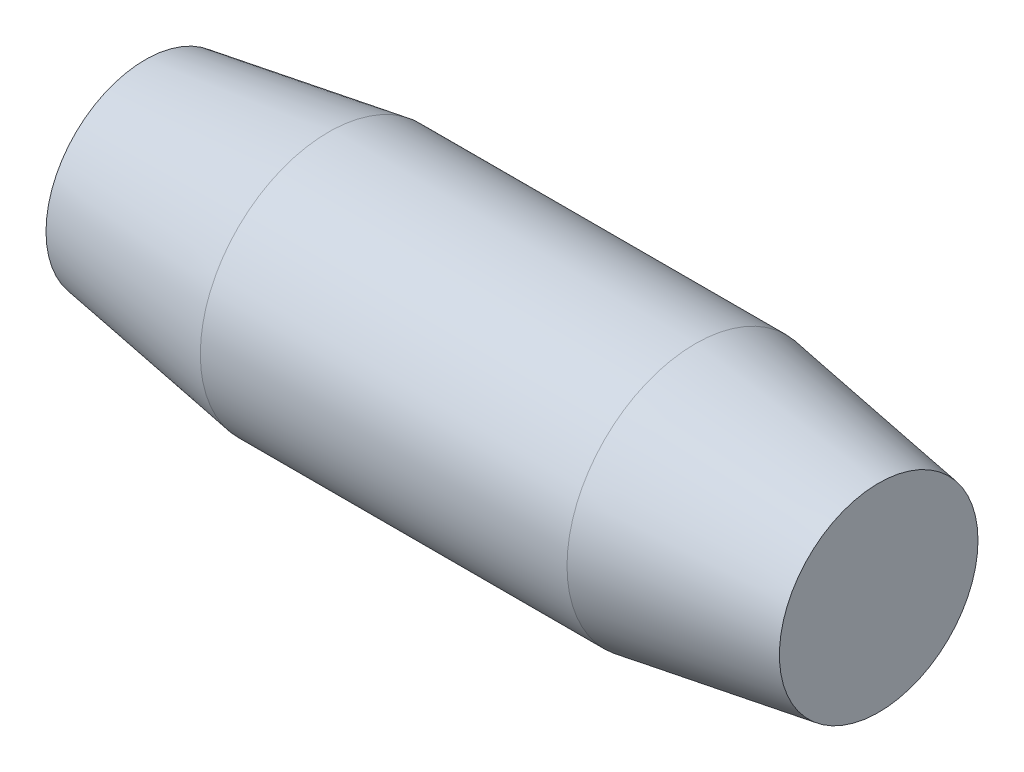
SolidWorks part; units mm, degrees
material "A-1"
ref_plane "Front Plane" through (0, 0, 0) normal (0, 0, 1) x (1, 0, 0)
ref_plane "Top Plane" through (0, 0, 0) normal (0, 1, 0) x (1, 0, 0)
ref_plane "Right Plane" through (0, 0, 0) normal (1, 0, 0) x (0, 0, -1)
sketch "Sketch1" plane through (0, 0, 0) normal (1, 0, 0) x (0, 0, -1)
  circle A0 centre (0, 0) radius 6.6675
  dimension "D1" = 13.335
extrude "Boss-Extrude1" add sketch "Sketch1" along normal mid plane 19.05
sketch "Sketch3" plane through (9.525, 0, 0) normal (1, 0, 0) x (0, 0, -1)
  circle A1 centre (0, 0) radius 6.6675
  circle A2 centre (0, 0) radius 6.6675
  dimension "D1" = 0
extrude "Boss-Extrude2" add sketch "Sketch3" along normal blind 9.525 draft 9
mirror "Mirror1" about plane through (0, 0, 0) normal (1, 0, 0) of "Boss-Extrude2"
